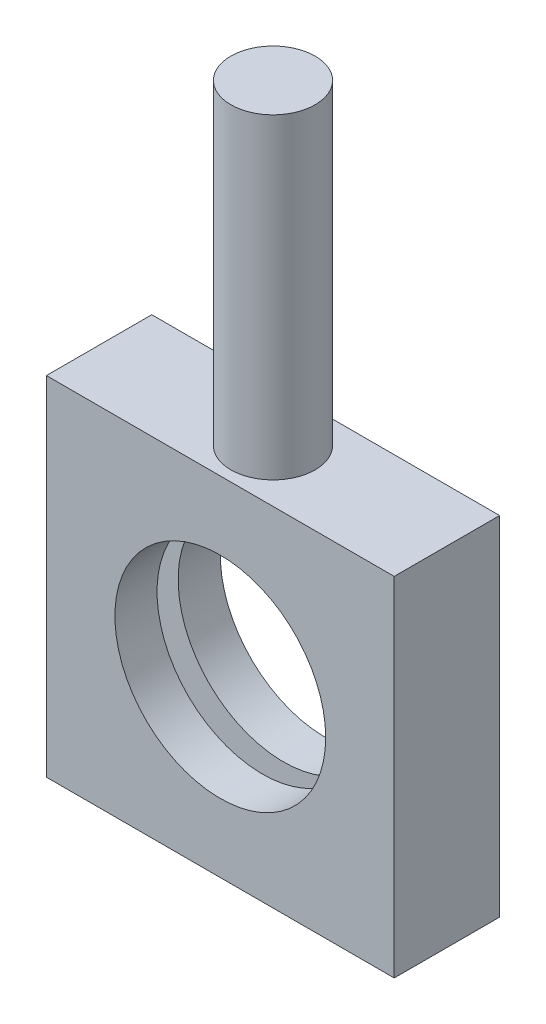
SolidWorks part; units mm, degrees
ref_plane "Front Plane" through (0, 0, 0) normal (0, 0, 1) x (1, 0, 0)
ref_plane "Top Plane" through (0, 0, 0) normal (0, 1, 0) x (1, 0, 0)
ref_plane "Right Plane" through (0, 0, 0) normal (1, 0, 0) x (0, 0, -1)
sketch "Sketch1" plane through (0, 0, 0) normal (0, 0, 1) x (1, 0, 0)
  line L1 (-12.0364, 21.0326) -> (20.9636, 21.0326)
  line L2 (-12.0364, 21.0326) -> (-12.0364, -11.9674)
  line L3 (-12.0364, -11.9674) -> (20.9636, -11.9674)
  line L4 (20.9636, 21.0326) -> (20.9636, -11.9674)
  dimension "D1" = 33
  dimension "D2" = 33
extrude "Boss-Extrude1" add sketch "Sketch1" along normal blind 10
shell "Shell1" thickness 4
sketch "Sketch3" plane through (0, 0, 10) normal (0, 0, 1) x (1, 0, 0)
  line L0 (20.9636, -11.9674) -> (20.9636, 21.0326) construction
  line L1 (-12.0364, -11.9674) -> (20.9636, -11.9674) construction
  circle A0 centre (4.4636, 4.5326) radius 10
  dimension "D1" = 20
  dimension "D2" = 16.5
  dimension "D3" = 16.5
extrude "Cut-Extrude1" cut sketch "Sketch3" against normal blind 10
sketch "Sketch5" plane through (0, 21.0326, 0) normal (0, 1, 0) x (1, 0, 0)
  line L0 (20.9636, 0) -> (-12.0364, 0) construction
  line L1 (20.9636, -10) -> (20.9636, 0) construction
  circle A0 centre (4.4636, -5) radius 4
  dimension "D3" = 8
  dimension "D1" = 5
  dimension "D2" = 16.5
extrude "Boss-Extrude2" add sketch "Sketch5" along normal blind 30
